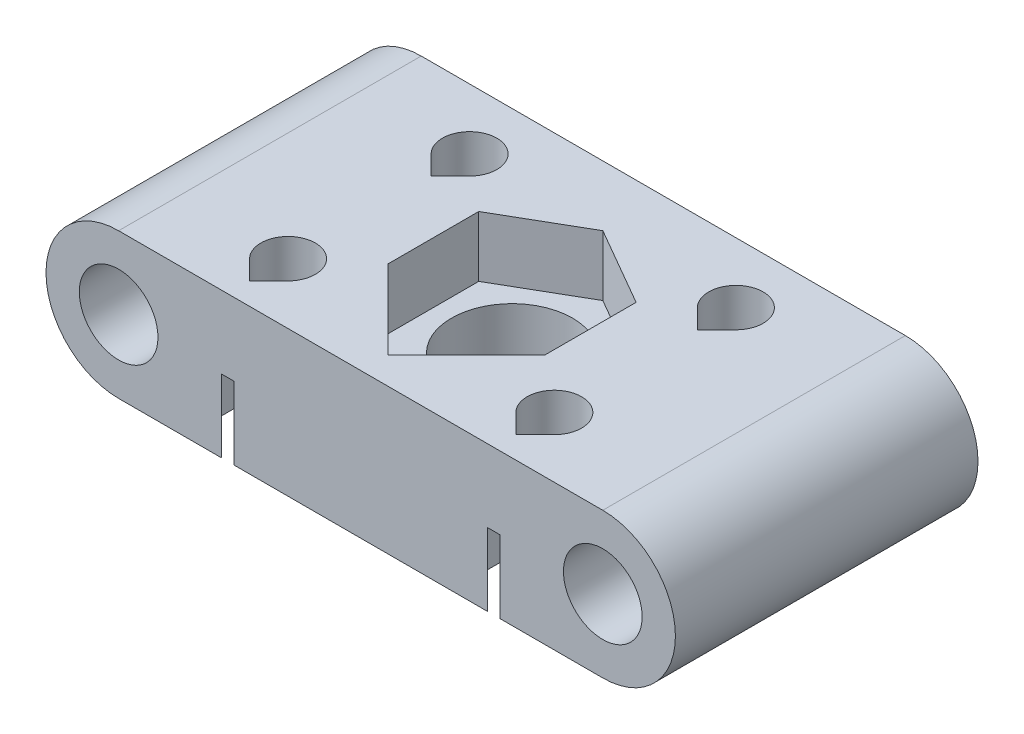
SolidWorks part; units mm, degrees
material "Printed PLA"
ref_plane "Front Plane" through (0, 0, 0) normal (0, 0, 1) x (1, 0, 0)
ref_plane "Top Plane" through (0, 0, 0) normal (0, 1, 0) x (1, 0, 0)
ref_plane "Right Plane" through (0, 0, 0) normal (1, 0, 0) x (0, 0, -1)
sketch "Sketch1" plane through (0, 0, 0) normal (0, 0, 1) x (1, 0, 0)
  line L0 (-20, 0) -> (20, 0) construction
  line L1 (-20, 6) -> (20, 6)
  line L2 (-20, -6) -> (20, -6)
  arc A0 (-20, 6) -> (-20, -6) centre (-20, 0) ccw
  arc A1 (20, -6) -> (20, 6) centre (20, 0) ccw
  circle A2 centre (20, 0) radius 3.25
  circle A3 centre (-20, 0) radius 3.25
  point P3 (0, 0)
  dimension "D2" = 6.5
  dimension "D1" = 40
  dimension "D3" = 12
extrude "Boss-Extrude1" add sketch "Sketch1" along normal mid plane 25
sketch "Sketch2" plane through (0, 6, 0) normal (0, 1, 0) x (1, 0, 0)
  line L0 (-3.5355, -3.5355) -> (0, -7.0711)
  line L1 (0, -7.0711) -> (3.5355, -3.5355)
  line L2 (0, 0) -> (0, -7.0711) construction
  arc A0 (3.5355, -3.5355) -> (-3.5355, -3.5355) centre (0, 0) ccw
  dimension "D1" = 5
extrude "Cut-Extrude1" cut sketch "Sketch2" against normal through all
sketch "Sketch3" plane through (0, 6, 0) normal (0, 1, 0) x (1, 0, 0)
  line L0 (-6.5, -3.7528) -> (0, -10.2528)
  line L1 (0, 7.5056) -> (-6.5, 3.7528)
  line L2 (-6.5, 3.7528) -> (-6.5, -3.7528)
  line L3 (-6.5, -3.7528) -> (0, -7.5056) construction
  line L4 (0, -7.5056) -> (6.5, -3.7528) construction
  line L5 (6.5, -3.7528) -> (6.5, 3.7528)
  line L6 (6.5, 3.7528) -> (0, 7.5056)
  line L7 (0, -10.2528) -> (6.5, -3.7528)
  circle A0 centre (0, 0) radius 6.5 construction
  dimension "D1" = 13
extrude "Cut-Extrude2" cut sketch "Sketch3" against normal blind 5
sketch "Sketch4" plane through (0, 6, 0) normal (0, 1, 0) x (1, 0, 0)
  line L0 (-9.409, 5.909) -> (-11, 4.318)
  line L1 (-11, 4.318) -> (-12.591, 5.909)
  line L2 (-11, 7.5) -> (-11, 4.318) construction
  line L3 (-11, 4.318) -> (-11.0968, 4.2676) construction
  line L4 (-11, 7.5) -> (11, 7.5) construction
  line L5 (0, 7.5) -> (0, 0) construction
  line L6 (0, 0) -> (-11, 0) construction
  line L7 (11, 4.318) -> (11.0968, 4.2676) construction
  line L8 (11, 7.5) -> (11, 4.318) construction
  line L9 (11, 4.318) -> (12.591, 5.909)
  line L10 (9.409, 5.909) -> (11, 4.318)
  line L11 (-9.409, -9.091) -> (-11, -10.682)
  line L12 (-11, -10.682) -> (-12.591, -9.091)
  line L13 (11, -10.682) -> (12.591, -9.091)
  line L14 (9.409, -9.091) -> (11, -10.682)
  line L15 (-11, -7.5) -> (-11, -10.682) construction
  line L16 (-11, -10.682) -> (-11.0968, -10.7324) construction
  line L17 (-11, -7.5) -> (11, -7.5) construction
  line L18 (11, -10.682) -> (11.0968, -10.7324) construction
  line L19 (11, -7.5) -> (11, -10.682) construction
  line L20 (-11, -7.5) -> (-11, 7.5) construction
  arc A0 (-9.409, 5.909) -> (-12.591, 5.909) centre (-11, 7.5) ccw
  arc A1 (9.409, 5.909) -> (12.591, 5.909) centre (11, 7.5) cw
  arc A2 (-9.409, -9.091) -> (-12.591, -9.091) centre (-11, -7.5) ccw
  arc A3 (9.409, -9.091) -> (12.591, -9.091) centre (11, -7.5) cw
  dimension "D1" = 4.5
  dimension "D2" = 22
  dimension "D3" = 15
  dimension "D4" = 2
extrude "Cut-Extrude3" cut sketch "Sketch4" against normal through all
sketch "Sketch5" plane through (0, -6, 0) normal (0, -1, 0) x (1, 0, 0)
  line L0 (-5.6569, 5.6569) -> (0, 11.3137)
  line L1 (0, 11.3137) -> (5.6569, 5.6569)
  line L2 (0, 11.3137) -> (0, 0) construction
  arc A0 (-5.6569, 5.6569) -> (5.6569, 5.6569) centre (0, 0) ccw
  dimension "D1" = 8
extrude "Cut-Extrude4" cut sketch "Sketch5" against normal blind 2
sketch "Sketch6" plane through (0, -6, 0) normal (0, -1, 0) x (1, 0, 0)
  line L0 (-14.5, 9.5207) -> (-11, 13.0207)
  line L1 (11, -3.4585) -> (7.5, -5.4793) construction
  line L2 (7.5, -5.4793) -> (7.5, -9.5207)
  line L3 (7.5, -9.5207) -> (11, -11.5415)
  line L4 (11, -11.5415) -> (14.5, -9.5207)
  line L5 (14.5, -9.5207) -> (14.5, -5.4793)
  line L6 (14.5, -5.4793) -> (11, -3.4585) construction
  line L7 (11, 11.5415) -> (7.5, 9.5207) construction
  line L8 (7.5, 9.5207) -> (7.5, 5.4793)
  line L9 (7.5, 5.4793) -> (11, 3.4585)
  line L10 (11, 3.4585) -> (14.5, 5.4793)
  line L11 (14.5, 5.4793) -> (14.5, 9.5207)
  line L12 (14.5, 9.5207) -> (11, 11.5415) construction
  line L13 (-11, 11.5415) -> (-14.5, 9.5207) construction
  line L14 (-14.5, 9.5207) -> (-14.5, 5.4793)
  line L15 (-14.5, 5.4793) -> (-11, 3.4585)
  line L16 (-11, 3.4585) -> (-7.5, 5.4793)
  line L17 (-7.5, 5.4793) -> (-7.5, 9.5207)
  line L18 (-7.5, 9.5207) -> (-11, 11.5415) construction
  line L19 (-11, -3.4585) -> (-14.5, -5.4793) construction
  line L20 (-14.5, -5.4793) -> (-14.5, -9.5207)
  line L21 (-14.5, -9.5207) -> (-11, -11.5415)
  line L22 (-11, -11.5415) -> (-7.5, -9.5207)
  line L23 (-7.5, -9.5207) -> (-7.5, -5.4793)
  line L24 (-7.5, -5.4793) -> (-11, -3.4585) construction
  line L25 (-11, 13.0207) -> (-7.5, 9.5207)
  line L26 (7.5, 9.5207) -> (11, 13.0207)
  line L27 (11, 13.0207) -> (14.5, 9.5207)
  line L28 (7.5, -5.4793) -> (11, -1.9793)
  line L29 (11, -1.9793) -> (14.5, -5.4793)
  line L30 (-14.5, -5.4793) -> (-11, -1.9793)
  line L31 (-11, -1.9793) -> (-7.5, -5.4793)
  circle A0 centre (11, -7.5) radius 3.5 construction
  circle A1 centre (11, 7.5) radius 3.5 construction
  circle A2 centre (-11, 7.5) radius 3.5 construction
  circle A3 centre (-11, -7.5) radius 3.5 construction
  dimension "D1" = 7
extrude "Cut-Extrude5" cut sketch "Sketch6" against normal blind 6
